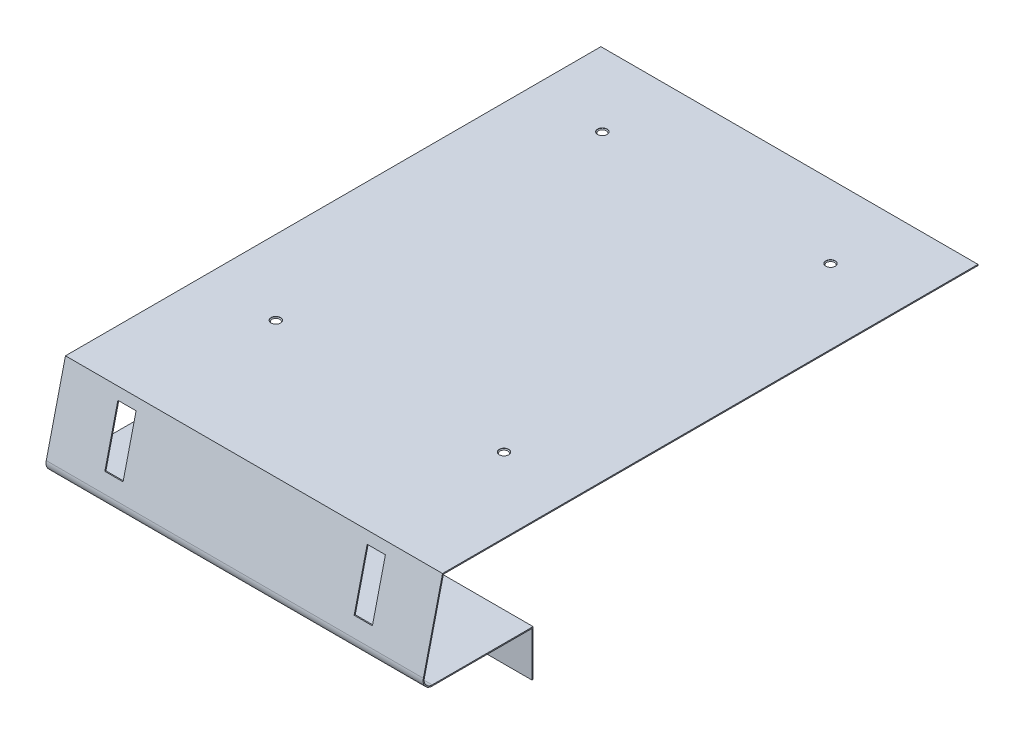
SolidWorks part; units mm, degrees
material "6061 합금"
ref_plane "정면" through (0, 0, 0) normal (0, 0, 1) x (1, 0, 0)
ref_plane "윗면" through (0, 0, 0) normal (0, 1, 0) x (1, 0, 0)
ref_plane "우측면" through (0, 0, 0) normal (1, 0, 0) x (0, 0, -1)
sketch "스케치1" plane through (0, 0, 0) normal (0, 1, 0) x (1, 0, 0)
  line L1 (-206.6, 294.06) -> (206.6, 294.06) construction
  line L2 (-206.6, 294.06) -> (-206.6, -294.06) construction
  line L3 (-206.6, -294.06) -> (206.6, -294.06) construction
  line L4 (206.6, 294.06) -> (206.6, -294.06) construction
  line L5 (-206.6, 294.06) -> (206.6, -294.06) construction
  line L6 (-206.6, -294.06) -> (206.6, 294.06) construction
  line L7 (-206.6, 294.06) -> (206.6, 294.06)
  line L9 (-206.6, -294.06) -> (206.6, -294.06)
  line L11 (-206.6, 294.06) -> (-206.6, -294.06)
  line L12 (-206.6, 294.06) -> (-206.6, -294.06) construction
  line L13 (206.6, 294.06) -> (206.6, -294.06)
  line L14 (206.6, 294.06) -> (206.6, -294.06) construction
  point P0 (0, 0)
  dimension "D1" = 588.12
  dimension "D2" = 413.2
  dimension "D3" = 0
extrude "보스-돌출1" add sketch "스케치1" along normal blind 1.2
sketch "스케치2" plane through (0, 0, 0) normal (1, 0, 0) x (0, 0, -1)
  line L9 (-294.06, 0) -> (-293.7759, 1.2) construction
  line L10 (-294.06, 1.2) -> (294.06, 1.2) construction
  line L11 (-294.06, 0) -> (294.06, 0) construction
  line L12 (-293.9572, 0) -> (-293.6731, 1.2)
  line L13 (-293.6731, 1.2) -> (-294.06, 1.2)
  line L14 (-294.06, 1.2) -> (-294.06, 0)
  line L15 (-294.06, 0) -> (-293.9572, 0)
  dimension "D1" = 76.68
  dimension "D2" = 0.1
extrude "컷-돌출1" cut sketch "스케치2" against normal through all both and the other way through all
sketch "스케치4" plane through (206.6, 0, 0) normal (1, 0, 0) x (0, 0, -1)
  line L0 (-323.4084, -100) -> (-191.7497, -100) construction
  line L1 (-293.9572, 0) -> (294.06, 0) construction
  line L2 (-293.9572, 0) -> (-314.72, -87.6961)
  line L3 (-293.9572, 0) -> (-293.6731, 1.2) construction
  line L4 (-304.9891, -100) -> (-195.6331, -100)
  line L5 (-195.6331, -100) -> (-195.6331, -149)
  line L6 (-292.7895, -0.2765) -> (-313.5523, -87.9726)
  line L7 (-304.9891, -98.8) -> (-194.4331, -98.8)
  line L8 (-194.4331, -98.8) -> (-194.4331, -149)
  line L9 (-292.7895, -0.2765) -> (-292.7241, 0)
  line L10 (-292.7241, 0) -> (-293.9572, 0)
  line L11 (-195.6331, -149) -> (-194.4331, -149)
  arc A0 (-314.72, -87.6961) -> (-304.9891, -100) centre (-304.9891, -90) ccw
  arc A1 (-313.5523, -87.9726) -> (-304.9891, -98.8) centre (-304.9891, -90) ccw
  point P13 (-317.6331, -100)
  dimension "D4" = 10
  dimension "D1" = 100
  dimension "D2" = 122
  dimension "D3" = 49
  dimension "D5" = 1.2
extrude "보스-돌출3" add sketch "스케치4" against normal up to vertex (413.2 mm away) up to point (-206.6, 0, 293.9572)
sketch "스케치5" plane through (0, 1.2, 0) normal (0, 1, 0) x (1, 0, 0)
  line L0 (206.6, 294.06) -> (-206.6, 294.06) construction
  line L1 (-206.6, 294.06) -> (206.6, 294.06)
  line L2 (-206.6, 294.06) -> (-206.6, 293.06)
  line L3 (-206.6, 293.06) -> (206.6, 293.06)
  line L4 (206.6, 294.06) -> (206.6, 293.06)
  line L5 (206.6, -293.6731) -> (206.6, 294.06) construction
  line L6 (-206.6, 294.06) -> (-206.6, -293.6731) construction
  dimension "D1" = 1
extrude "컷-돌출2" cut sketch "스케치5" against normal up to next
sketch "스케치6" plane through (0, 1.2, 0) normal (0, 1, 0) x (1, 0, 0)
  line L0 (-206.6, -194.74) -> (206.6, -194.74) construction
  line L1 (-206.6, 293.06) -> (-206.6, -293.6731) construction
  line L2 (206.6, -293.6731) -> (206.6, 293.06) construction
  line L4 (-206.6, -164.74) -> (206.6, -164.74) construction
  line L5 (-110, -164.74) -> (-110, 293.06) construction
  line L6 (-206.6, 293.06) -> (206.6, 293.06) construction
  line L7 (-140, -164.74) -> (-140, 293.06) construction
  line L8 (110, -164.74) -> (110, 293.06) construction
  line L9 (140, 293.06) -> (140, -164.74) construction
  line L10 (-125, -164.74) -> (-125, 293.06) construction
  line L11 (125, 293.06) -> (125, -164.74) construction
  line L13 (-206.6, 293.06) -> (206.6, 293.06) construction
  point P24 (-125, -144.74)
  point P25 (125, -144.74)
  point P26 (125, 213.06)
  point P27 (-125, 213.06)
  dimension "D2" = 30
  dimension "D3" = 96.6
  dimension "D4" = 30
  dimension "D5" = 96.6
  dimension "D6" = 30
  dimension "D7" = 15
  dimension "D8" = 15
  dimension "D9" = 80
  dimension "D10" = 80
  dimension "D11" = 20
  dimension "D12" = 20
  dimension "D13" = 487.8
hole_wizard "M5 접시 머리 나사용 카운터싱크1" positions "스케치7" profile "스케치8" countersink size "M5" standard "ISO" end condition up to next
sketch "스케치7" plane through (0, 1.2, 0) normal (0, 1, 0) x (1, 0, 0)
  point P0 (-125, 213.06)
  point P3 (125, 213.06)
  point P6 (125, -144.74)
  point P9 (-125, -144.74)
sketch "스케치8" plane through (-125, 1.2, -213.06) normal (1, 0, 0) x (0, 0, 1)
  line L0 (0, 0) -> (0, 1.2)
  line L1 (0, 1.2) -> (2.75, 1.2)
  line L2 (2.75, 1.2) -> (2.75, 2.75)
  line L3 (2.75, 2.75) -> (5.2, 0.3)
  line L4 (5.2, 0.3) -> (5.2, 0)
  line L6 (5.2, 0) -> (0, 0)
  line L7 (-2.75, 2.75) -> (-5.2, 0.3) construction
  line L11 (0, -6.35) -> (0, 107.95) construction
  dimension "관통 구멍 지름" = 5.5
  dimension "관통 구멍 깊이" = 1.2
  dimension "카운터싱크 지름" = 10.4
  dimension "카운터싱크 각도" = 90
  dimension "머리 여유값" = 0.3
sketch "스케치10" plane through (0, 0, 195.6331) normal (0, 0, 1) x (1, 0, 0)
  line L0 (0, 0) -> (0, -186.147) construction
  line L1 (-206.6, -149) -> (206.6, -149) construction
  line L2 (-40, -149) -> (40, -149)
  line L3 (-40, -149) -> (-40, -100)
  line L4 (-40, -100) -> (40, -100)
  line L5 (40, -149) -> (40, -100)
  line L6 (-206.6, -100) -> (206.6, -100) construction
  dimension "D1" = 80
  dimension "D2" = 40
extrude "컷-돌출3" cut sketch "스케치10" against normal up to next
ref_plane "평면1" through (0, 0, 320) normal (0, 0, 1) x (1, 0, 0)
sketch "스케치11" plane through (0, 0, 320) normal (0, 0, 1) x (1, 0, 0)
  line L2 (-206.6, 0) -> (206.6, 0) construction
  line L3 (-206.6, 0) -> (206.6, 0)
  line L8 (0, 0) -> (0, -56.567) construction
  line L21 (-206.6, -87.6961) -> (-206.6, 1.2) construction
  line L22 (-146.6, -10) -> (-126.6, -10)
  line L26 (-146.6, -10) -> (-146.6, -70)
  line L27 (-146.6, -70) -> (-126.6, -70)
  line L28 (-126.6, -10) -> (-126.6, -70)
  line L29 (146.6, -70) -> (126.6, -70)
  line L30 (126.6, -10) -> (126.6, -70)
  line L31 (146.6, -10) -> (126.6, -10)
  line L32 (146.6, -10) -> (146.6, -70)
  line L33 (-206.6, -87.6961) -> (206.6, -87.6961) construction
  dimension "D1" = 60
  dimension "D2" = 20
  dimension "D3" = 60
  dimension "D4" = 10
  dimension "D5" = 17.6961
extrude "컷-돌출4" cut sketch "스케치11" against normal up to next
sketch "스케치12" plane through (-146.6, 0, 0) normal (1, 0, 0) x (0, 0, -1)
  line L0 (-295.0916, -10) -> (-296.2594, -9.7235)
  line L1 (-314.72, -87.6961) -> (-293.6731, 1.2) construction
  line L2 (-296.2594, -9.7235) -> (-296.3248, -10)
  line L3 (-310.5303, -70) -> (-309.3169, -70.0835)
  line L4 (-296.3248, -10) -> (-310.5303, -70)
  line L5 (-310.5303, -70) -> (-309.2972, -70)
  line L6 (-309.2972, -70) -> (-295.0916, -10)
  line L7 (-295.0916, -10) -> (-296.3248, -10)
  line L8 (-296.3248, -10) -> (-310.5303, -70)
  line L10 (-309.2972, -70) -> (-295.0916, -10)
  line L12 (-313.5523, -87.9726) -> (-292.7241, 0) construction
  line L13 (-309.3169, -70.0835) -> (-309.2972, -70)
  dimension "D1" = 0
extrude "컷-돌출5" cut sketch "스케치12" along normal blind 20
mirror "대칭 복사2" about plane through (0, 0, 0) normal (1, 0, 0) of "컷-돌출5"
equation "\"D2@스케치10\"=\"D1@스케치10\"/2"
